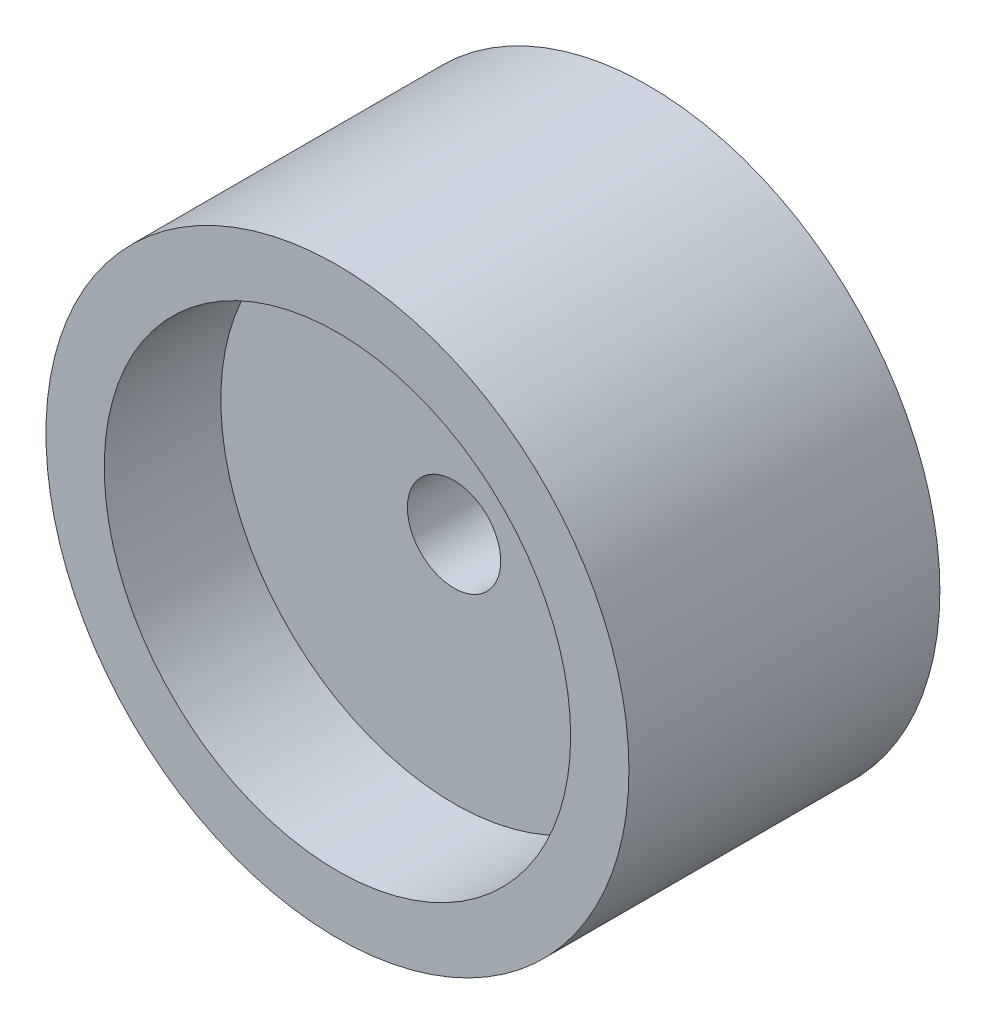
SolidWorks part; units mm, degrees
ref_plane "정면" through (0, 0, 0) normal (0, 0, 1) x (1, 0, 0)
ref_plane "윗면" through (0, 0, 0) normal (0, 1, 0) x (1, 0, 0)
ref_plane "우측면" through (0, 0, 0) normal (1, 0, 0) x (0, 0, -1)
sketch "스케치1" plane through (0, 0, 0) normal (0, 0, 1) x (1, 0, 0)
  circle A0 centre (0, 0) radius 7.5
  dimension "D1" = 15
extrude "보스-돌출1" add sketch "스케치1" along normal blind 8
sketch "스케치2" plane through (0, 0, 8) normal (0, 0, 1) x (1, 0, 0)
  circle A0 centre (0, 0) radius 6
  dimension "D1" = 12
extrude "컷-돌출1" cut sketch "스케치2" against normal blind 3
hole_wizard "M2 소켓 머리 캡 나사용 카운터보어1" positions "스케치3" profile "스케치4" counterbore size "M2" standard "KS"
sketch "스케치3" plane through (0, 0, 0) normal (0, 0, -1) x (-1, 0, 0)
  point P0 (0, 0)
sketch "스케치4" plane through (0, 0, 0) normal (1, 0, 0) x (0, 1, 0)
  line L0 (0, 0) -> (0, 5.721)
  line L1 (0, 5.721) -> (1.2, 5)
  line L2 (1.2, 5) -> (1.2, 2)
  line L3 (1.2, 2) -> (2.25, 2)
  line L5 (2.25, 2) -> (2.25, 0.025)
  line L6 (2.25, 0.025) -> (2.275, 0)
  line L7 (2.275, 0) -> (0, 0)
  line L8 (-2.25, 0.025) -> (-2.275, 0) construction
  line L10 (0, 5.721) -> (-1.2, 5) construction
  line L11 (0, -6.35) -> (0, 107.95) construction
  dimension "구멍 지름" = 2.4
  dimension "구멍 깊이" = 5
  dimension "카운터보어 지름" = 4.5
  dimension "카운터보어 깊이" = 2
  dimension "표면 카운터싱크 지름" = 4.55
  dimension "표면 카운터싱크 각도" = 90
  dimension "드릴 각도" = 118
